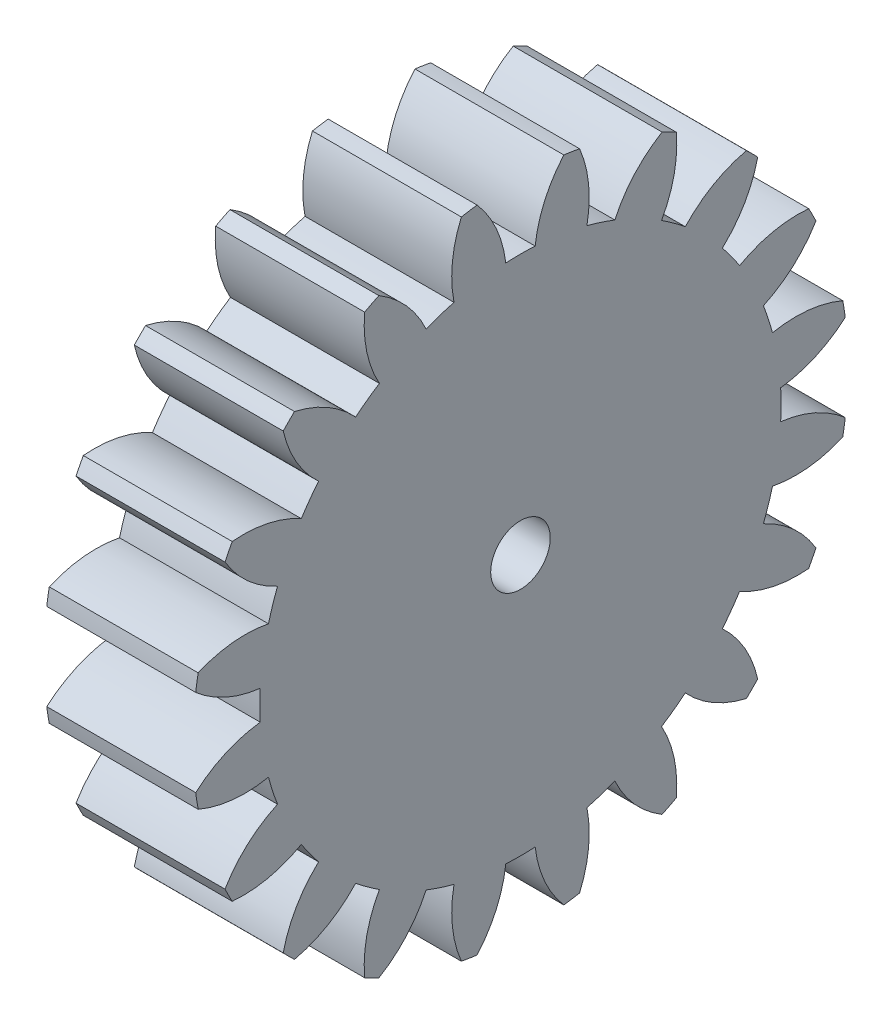
SolidWorks part; units mm, degrees
ref_plane "Plane1" through (0, 0, 0) normal (0, 0, 1) x (1, 0, 0)
ref_plane "Plane2" through (0, 0, 0) normal (0, 1, 0) x (1, 0, 0)
ref_plane "Plane3" through (0, 0, 0) normal (1, 0, 0) x (0, 0, -1)
other "Configuration Table"
sketch "HoldingSke" plane through (0, 0, 0) normal (0, 1, 0) x (1, 0, 0)
  line L0 (0, 0) -> (0.4698, -0.171)
  line L1 (-15, 0) -> (100, 0) construction
  line L2 (0, 0) -> (-2.1039, 2.3779)
  line L3 (0, 0) -> (-11.863, 4.5341)
  line L4 (0, 0) -> (8.1152, 2.9537)
  line L5 (0, 0) -> (-46.8476, -17.4728)
  line L6 (0, 0) -> (-8.2896, -5.593)
  line L7 (-2.1039, 2.3779) -> (8.6586, 51.2059)
  line L8 (-76.2, 54.61) -> (-75.5, 54.61)
  line L9 (-71.009, 38.7566) -> (-53.1078, 45.2721)
  line L10 (-76.2, 71.12) -> (104.1128, 71.12)
  line L11 (0, 0) -> (-10, 0)
  line L12 (-76.2, 101.6) -> (-76.133, 101.6)
  line L13 (24.9733, 27.94) -> (52.9518, 28.4284)
  line L14 (24.9733, 27.94) -> (24.9743, 27.94)
  line L15 (24.9733, 27.94) -> (100.4006, 29.5858)
  line L16 (-63.627, -2) -> (-12.827, -2)
  circle A0 centre (0, 0) radius 2
  circle A1 centre (0, 0) radius 17.499
  circle A2 centre (0, 0) radius 37.5
  circle A3 centre (0, 0) radius 2
  dimension "MHD" = 34.998
  dimension "Hub_dia" = 75
  dimension "Bore" = 4
  dimension "MBD" = 4
  dimension "Num_teeth" = 20
  dimension "Pitch" = 0.5
  dimension "Overall_len" = 50
  dimension "Show_teeth" = 20
  dimension "Thickness" = 10
  dimension "OAL" = 50.0001
  dimension "T_dim" = 0.7
  dimension "Ap" = 20
  dimension "H" = 19.05
  dimension "Pitch_radius" = 180.3128
  dimension "Width" = 10
  dimension "Backlash" = 0.067
  dimension "Addendum_fac" = 1
  dimension "Dedendum_fac" = 1.25
  dimension "Clearance_fac" = 0.25
  dimension "Dedendum_add" = 0.001
  dimension "Module" = 2
sketch "BasProSke" plane through (0, 0, 0) normal (0, 1, 0) x (1, 0, 0)
  line L0 (-10, 0) -> (60, 0) construction
  line L1 (0, 0) -> (0, 22)
  line L2 (0, 0) -> (10, 0)
  line L3 (10, 0) -> (10, 22)
  line L4 (10, 22) -> (0, 22)
  dimension "Thickness" = 10
  dimension "Diameter" = 44
revolve "Base-Revolve" add sketch "BasProSke" angle 360 about L0
sketch "TooCutSke" plane through (0, 0, 0) normal (1, 0, 0) x (0, 0, -1)
  line L1 (0, 0) -> (0, 107) construction
  line L2 (0, 0) -> (-1.6864, 19.9288) construction
  line L3 (0, 0) -> (-6.2409, 39.4033) construction
  line L4 (-1.6864, 19.9288) -> (-3.1204, 19.7016) construction
  arc A0 (0.9862, 17.4712) -> (-0.9862, 17.4712) centre (0, 0) ccw
  arc A1 (2.9329, 21.8293) -> (-2.9329, 21.8293) centre (0, 0) ccw
  circle A2 centre (0, 0) radius 20 construction
  circle A3 centre (0, 0) radius 18.7939 construction
  arc A4 (-0.9862, 17.4712) -> (-2.9329, 21.8293) centre (-8.9313, 16.536) ccw
  arc A5 (2.9329, 21.8293) -> (0.9862, 17.4712) centre (8.9313, 16.536) ccw
  dimension "Root_dia" = 34.998
  dimension "Overcut_dia" = 44.0508
  dimension "Pitch_dia" = 40
  dimension "Base_dia" = 37.5877
  dimension "Flank_rad" = 8
  dimension "Half_ang" = 9
  dimension "Half_CT" = 1.4519
extrude "ToothCut" cut sketch "TooCutSke" along normal through all
fillet "Breaks" [suppressed] radius 0.04
fillet "RootFillets" [suppressed] radius 0.501
pattern_circular "TeethCuts" count 20 every 18 about axis through (-10, 0, 0) along (1, 0, 0) of "ToothCut", "RootFillets", "Breaks"
sketch "HubNeaOneSke" plane through (0, 0, 0) normal (-1, 0, 0) x (0, 0, 1)
  circle A0 centre (0, 0) radius 17.499
  dimension "Diameter" = 34.998
extrude "HubNearOne" [suppressed] add sketch "HubNeaOneSke" along normal blind 40.0001
sketch "HubNeaBotSke" plane through (0, 0, 0) normal (-1, 0, 0) x (0, 0, 1)
  circle A0 centre (0, 0) radius 17.499
  dimension "Diameter" = 34.998
extrude "HubNearBoth" [suppressed] add sketch "HubNeaBotSke" along normal blind 20
ref_plane "FarPln" through (10, 0, 0) normal (1, 0, 0) x (0, 0, -1)
sketch "HubFarSke" plane through (10, 0, 0) normal (1, 0, 0) x (0, 0, -1)
  circle A0 centre (0, 0) radius 17.499
  dimension "Diameter" = 34.998
extrude "HubFar" [suppressed] add sketch "HubFarSke" along normal blind 20
sketch "BorSke" plane through (0, 0, 0) normal (1, 0, 0) x (0, 0, -1)
  circle A0 centre (0, 0) radius 2
  dimension "Diameter" = 4
extrude "Bore" cut sketch "BorSke" along normal mid plane 100.0001
sketch "KeySke" plane through (0, 0, 0) normal (1, 0, 0) x (0, 0, -1)
  line L0 (-0.8, 0) -> (-0.8, 2.7)
  line L1 (-0.8, 2.7) -> (0.8, 2.7)
  line L2 (0.8, 2.7) -> (0.8, 0)
  line L3 (0, 0) -> (0, 34) construction
  line L4 (-0.8, 0) -> (0.8, 0)
  dimension "Offset" = 2.7
  dimension "Width" = 1.6
extrude "Keyway" [suppressed] cut sketch "KeySke" along normal mid plane 100.0001
pattern_circular "Keyway2" [suppressed] count 2 every 90 about axis through (-10, 0, 0) along (1, 0, 0)
equation "' \"Module@HoldingSke\" = 6.35"
equation "' \"Num_teeth@HoldingSke\" = 12"
equation "' \"Ap@HoldingSke\" =  20"
equation "' \"Ap@HoldingSke\" = 20"
equation "' \"Width@HoldingSke\" = 0.5 * 25.4"
equation "' \"Hub_dia@HoldingSke\"= 1 * 25.4"
equation "' \"Hub_dia@HoldingSke\" = 1 * 25.4"
equation "' \"Overall_len@HoldingSke\" = 1.0 * 25.4"
equation "' \"Bore@HoldingSke\" = 0.75 * 25.4"
equation "' \"T_dim@HoldingSke\" = 0.1 * 25.4"
equation "' \"Width@KeySke\" = 0.25 * 25.4"
equation "' \"Show_teeth@HoldingSke\" = 13"
equation "' \"Backlash@HoldingSke\" = 0.009 * 25.4"
equation "' \"Addendum_fac@HoldingSke\" = 1.0"
equation "' \"Dedendum_fac@HoldingSke\" = 1.25"
equation "' \"Dedendum_add@HoldingSke\" = 0.00005 * 25.4"
equation "' \"Clearance_fac@HoldingSke\" = 0.25"
equation "\"Pitch@HoldingSke\" = 1 / \"Module@HoldingSke\""
equation "\"Overcut_dia@TooCutSke\" = (\"Num_teeth@HoldingSke\" + 2 * \"Addendum_fac@HoldingSke\") / \"Pitch@HoldingSke\" + 0.002 * 25.4"
equation "\"Pitch_dia@TooCutSke\" = \"Num_teeth@HoldingSke\" / \"Pitch@HoldingSke\""
equation "\"Base_dia@TooCutSke\" = \"Num_teeth@HoldingSke\" / \"Pitch@HoldingSke\" * cos((\"Ap@HoldingSke\"  * 3.14159265 / 180))"
equation "\"Root_dia@TooCutSke\" = (\"Num_teeth@HoldingSke\" + 2) / \"Pitch@HoldingSke\" - 2 * (\"Addendum_fac@HoldingSke\" + \"Dedendum_fac@HoldingSke\") / \"Pitch@HoldingSke\" - \"Dedendum_add@HoldingSke\" * 2"
equation "\"Half_ang@TooCutSke\" = 180 / \"Num_teeth@HoldingSke\""
equation "\"Half_CT@TooCutSke\" = \"Num_teeth@HoldingSke\" / \"Pitch@HoldingSke\" * sin((3.14159265 / 2 / \"Num_teeth@HoldingSke\")) / 2 - 7 * \"Backlash@HoldingSke\" / 4"
equation "\"Flank_rad@TooCutSke\" = \"Num_teeth@HoldingSke\" / \"Pitch@HoldingSke\" / 5"
equation "\"Radius@RootFillets\" = \"Clearance_fac@HoldingSke\" / \"Pitch@HoldingSke\" + \"Dedendum_add@HoldingSke\""
equation "\"Break_rad@Breaks\" = 0.02 / \"Pitch@HoldingSke\""
equation "\"Thickness@HoldingSke\" = \"Width@HoldingSke\""
equation "\"OAL@HoldingSke\" = \"Thickness@HoldingSke\""
equation "\"MHD@HoldingSke\" = (\"Num_teeth@HoldingSke\" + 2) / \"Pitch@HoldingSke\" - 2 * (\"Addendum_fac@HoldingSke\" + \"Dedendum_fac@HoldingSke\")  / \"Pitch@HoldingSke\" - \"Dedendum_add@HoldingSke\" * 2"
equation "\"MBD@HoldingSke\" = (\"Num_teeth@HoldingSke\" + 2) / \"Pitch@HoldingSke\" - 2 * (\"Addendum_fac@HoldingSke\" + \"Dedendum_fac@HoldingSke\")  / \"Pitch@HoldingSke\" - \"Dedendum_add@HoldingSke\" * 2 - 0.002 * 25.4"
equation "\"MHD@HoldingSke\" = ((sgn( \"MHD@HoldingSke\" - \"Hub_dia@HoldingSke\" )-1)*( \"MHD@HoldingSke\" - \"Hub_dia@HoldingSke\" ))/-2+ \"Hub_dia@HoldingSke\""
equation "\"MBD@HoldingSke\" = ((sgn( \"MBD@HoldingSke\" - \"Bore@HoldingSke\" )-1)*( \"MBD@HoldingSke\" - \"Bore@HoldingSke\" ))/-2+ \"Bore@HoldingSke\""
equation "\"OAL@HoldingSke\" = ((sgn( \"OAL@HoldingSke\" - \"Overall_len@HoldingSke\" )+1)*( \"OAL@HoldingSke\" - \"Overall_len@HoldingSke\" ))/2 + \"Overall_len@HoldingSke\" + 0.000002 * 25.4"
equation "\"Num_teeth@TeethCuts\" = int( \"Show_teeth@HoldingSke\" ) + 1"
equation "\"Num_teeth@TeethCuts\" = ((sgn( \"Num_teeth@TeethCuts\" - \"Num_teeth@HoldingSke\" )-1)*( \"Num_teeth@TeethCuts\" - \"Num_teeth@HoldingSke\" ))/-2+ \"Num_teeth@HoldingSke\""
equation "\"Num_teeth@TeethCuts\" = ((sgn( \"Num_teeth@TeethCuts\" - 2.0)+1)*( \"Num_teeth@TeethCuts\" - 2.0))/2 +2.0"
equation "\"Angle@TeethCuts\" = 360.0 / \"Num_teeth@HoldingSke\""
equation "\"Diameter@BasProSke\" = (\"Num_teeth@HoldingSke\" + 2 * \"Addendum_fac@HoldingSke\") / \"Pitch@HoldingSke\""
equation "\"Thickness@BasProSke\"  = \"Thickness@HoldingSke\""
equation "' \"Fillet_rad@BasProSke\" =  \"Thickness@HoldingSke\" * 0.05"
equation "' \"Fillet_rad@BasProSke\" = \"Thickness@HoldingSke\" * 0.05"
equation "\"MHD@HoldingSke\" = ((sgn( \"MHD@HoldingSke\" - \"Root_dia@TooCutSke\" )-1)*( \"MHD@HoldingSke\" - \"Root_dia@TooCutSke\" ))/-2+ \"Root_dia@TooCutSke\""
equation "\"Diameter@HubNeaOneSke\" = \"MHD@HoldingSke\""
equation "\"Length@HubNearOne\" = \"OAL@HoldingSke\" - \"Thickness@BasProSke\""
equation "\"Diameter@HubNeaBotSke\" = \"MHD@HoldingSke\""
equation "\"Length@HubNearBoth\" = ( \"OAL@HoldingSke\" - \"Thickness@BasProSke\" ) / 2.0"
equation "\"Thickness@FarPln\" = \"Thickness@BasProSke\""
equation "\"Diameter@HubFarSke\" = \"MHD@HoldingSke\""
equation "\"Length@HubFar\" = ( \"OAL@HoldingSke\" - \"Thickness@BasProSke\" ) / 2.0"
equation "\"Diameter@BorSke\" = \"MBD@HoldingSke\""
equation "\"D1@Bore\" = \"OAL@HoldingSke\" * 2.0"
equation "\"D1@Keyway\" = \"OAL@HoldingSke\" * 2.0"
equation "\"Offset@KeySke\" = \"T_dim@HoldingSke\" + \"MBD@HoldingSke\" / 2.0"
